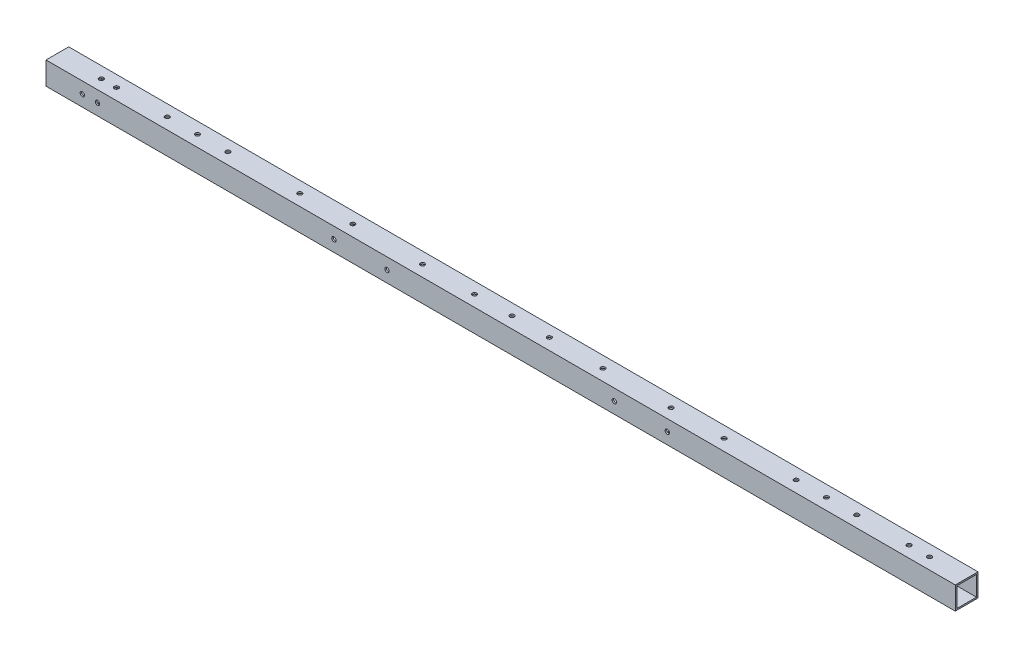
SolidWorks part; units mm, degrees
material "Thornel Mat VMA"
ref_plane "前视基准面" through (0, 0, 0) normal (0, 0, 1) x (1, 0, 0)
ref_plane "上视基准面" through (0, 0, 0) normal (0, 1, 0) x (1, 0, 0)
ref_plane "右视基准面" through (0, 0, 0) normal (1, 0, 0) x (0, 0, -1)
other "Configuration Table"
sketch "草图1" plane through (0, 0, 0) normal (1, 0, 0) x (0, 0, -1)
  line L0 (-6.5, -6.5) -> (-6.5, 6.5)
  line L1 (-7.5, -7.5) -> (7.5, -7.5)
  line L2 (-7.5, -7.5) -> (-7.5, 7.5)
  line L3 (-7.5, 7.5) -> (7.5, 7.5)
  line L4 (7.5, -7.5) -> (7.5, 7.5)
  line L5 (-7.5, -7.5) -> (7.5, 7.5) construction
  line L6 (-7.5, 7.5) -> (7.5, -7.5) construction
  line L7 (-6.5, 6.5) -> (6.5, 6.5)
  line L8 (6.5, -6.5) -> (6.5, 6.5)
  line L9 (-6.5, -6.5) -> (6.5, -6.5)
  point P0 (0, 0)
  dimension "D1" = 15
  dimension "D2" = 15
  dimension "D3" = 1
extrude "凸台-拉伸1" add sketch "草图1" along normal blind 600
sketch "草图3" plane through (0, 0, -7.5) normal (0, 0, -1) x (-1, 0, 0)
  circle A0 centre (-375, 0) radius 1.45 construction
  circle A1 centre (-410, 0) radius 1.45 construction
  circle A2 centre (-375, 0) radius 1.45
  circle A3 centre (-410, 0) radius 1.45
  circle A6 centre (-190, 0) radius 1.45 construction
  circle A7 centre (-225, 0) radius 1.45 construction
  circle A10 centre (-190, 0) radius 1.45
  circle A11 centre (-225, 0) radius 1.45
  circle A12 centre (-34, 0) radius 1.45 construction
  circle A13 centre (-24, 0) radius 1.45 construction
  circle A14 centre (-34, 0) radius 1.45
  circle A15 centre (-24, 0) radius 1.45
extrude "切除-拉伸2" cut sketch "草图3" against normal through all
sketch "草图4" plane through (0, 7.5, 0) normal (0, 1, 0) x (1, 0, 0)
  line L0 (195, 0) -> (241, 0) construction
  circle A0 centre (575.5, 0) radius 1.45 construction
  circle A1 centre (562, 0) radius 1.45 construction
  circle A2 centre (440, 0) radius 1.45 construction
  circle A3 centre (405, 0) radius 1.45 construction
  circle A4 centre (324.7, 0) radius 1.45 construction
  circle A5 centre (300, 0) radius 1.45 construction
  circle A6 centre (275.3, 0) radius 1.45 construction
  circle A7 centre (195, 0) radius 1.45 construction
  circle A8 centre (160, 0) radius 1.45 construction
  circle A9 centre (39, 0) radius 1.45 construction
  circle A10 centre (29, 0) radius 1.45 construction
  circle A11 centre (575.5, 0) radius 1.45
  circle A12 centre (562, 0) radius 1.45
  circle A13 centre (440, 0) radius 1.45
  circle A14 centre (405, 0) radius 1.45
  circle A15 centre (324.7, 0) radius 1.45
  circle A16 centre (300, 0) radius 1.45
  circle A17 centre (275.3, 0) radius 1.45
  circle A18 centre (195, 0) radius 1.45
  circle A19 centre (160, 0) radius 1.45
  circle A20 centre (39, 0) radius 1.45
  circle A21 centre (29, 0) radius 1.45
  circle A22 centre (527.5, 0) radius 1.45 construction
  circle A23 centre (507.5, 0) radius 1.45 construction
  circle A24 centre (487.5, 0) radius 1.45 construction
  circle A25 centre (112.5, 0) radius 1.45 construction
  circle A26 centre (92.5, 0) radius 1.45 construction
  circle A27 centre (72.5, 0) radius 1.45 construction
  circle A28 centre (527.5, 0) radius 1.45
  circle A29 centre (507.5, 0) radius 1.45
  circle A30 centre (487.5, 0) radius 1.45
  circle A31 centre (112.5, 0) radius 1.45
  circle A32 centre (92.5, 0) radius 1.45
  circle A33 centre (72.5, 0) radius 1.45
  circle A34 centre (360, 0) radius 1.45 construction
  circle A35 centre (360, 0) radius 1.45
  circle A36 centre (241, 0) radius 1.45
  dimension "D2" = 2.9
  dimension "D1" = 46
extrude "切除-拉伸3" cut sketch "草图4" against normal through all
